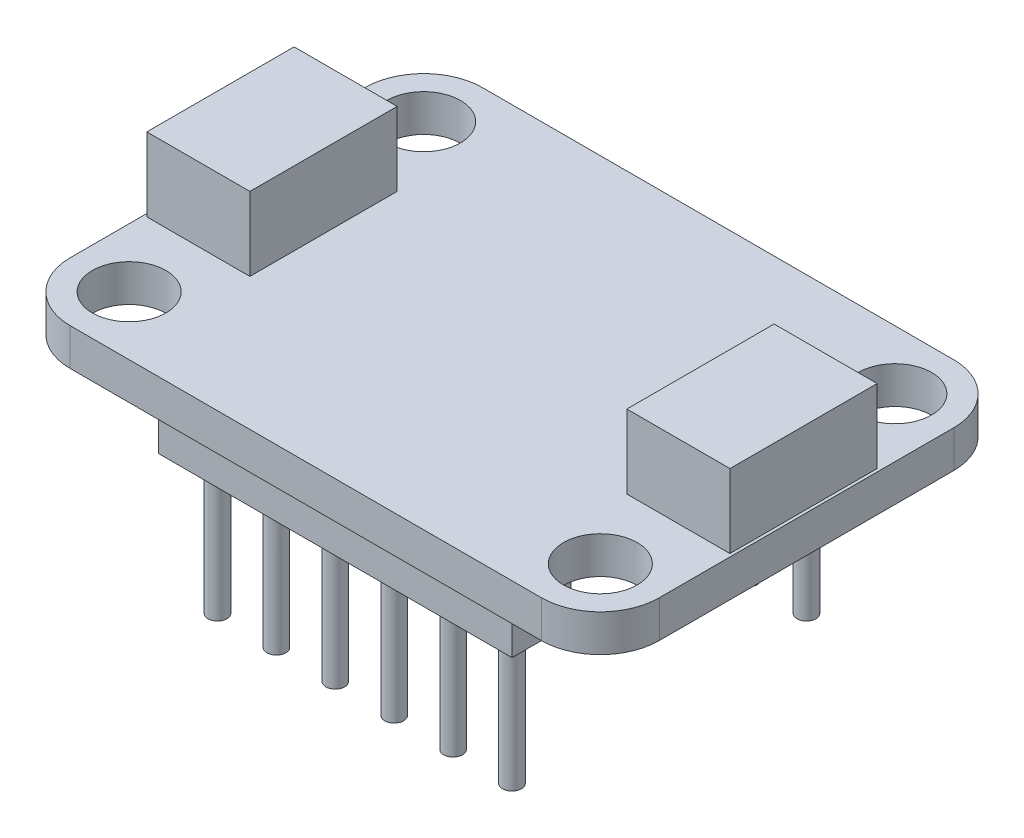
SolidWorks part; units mm, degrees
ref_plane "Front Plane" through (0, 0, 0) normal (0, 0, 1) x (1, 0, 0)
ref_plane "Top Plane" through (0, 0, 0) normal (0, 1, 0) x (1, 0, 0)
ref_plane "Right Plane" through (0, 0, 0) normal (1, 0, 0) x (0, 0, -1)
sketch "Sketch1" plane through (0, 0, 0) normal (0, 1, 0) x (1, 0, 0)
  line L1 (-12.7, -8.89) -> (12.7, -8.89)
  line L2 (-12.7, -8.89) -> (-12.7, 8.89)
  line L3 (-12.7, 8.89) -> (12.7, 8.89)
  line L4 (12.7, -8.89) -> (12.7, 8.89)
  line L5 (-12.7, -8.89) -> (12.7, 8.89) construction
  line L6 (-12.7, 8.89) -> (12.7, -8.89) construction
  point P0 (0, 0)
  dimension "D1" = 25.4
  dimension "D2" = 17.78
extrude "Boss-Extrude1" add sketch "Sketch1" along normal blind 1.6002
sketch "Sketch2" plane through (0, 1.6002, 0) normal (0, 1, 0) x (1, 0, 0)
  line L0 (12.7, 8.89) -> (-12.7, 8.89) construction
  line L1 (-10.16, -6.35) -> (10.16, -6.35) construction
  line L2 (-10.16, -6.35) -> (-10.16, 6.35) construction
  line L3 (-10.16, 6.35) -> (10.16, 6.35) construction
  line L4 (10.16, -6.35) -> (10.16, 6.35) construction
  line L5 (-10.16, -6.35) -> (10.16, 6.35) construction
  line L6 (-10.16, 6.35) -> (10.16, -6.35) construction
  line L7 (-12.7, 8.89) -> (-12.7, -8.89) construction
  line L8 (12.7, -8.89) -> (12.7, 8.89) construction
  line L9 (-12.7, -8.89) -> (12.7, -8.89) construction
  line L10 (-12.7, 6.35) -> (-12.7, 8.89)
  line L11 (-12.7, 8.89) -> (-10.16, 8.89)
  line L12 (10.16, 8.89) -> (12.7, 8.89)
  line L13 (12.7, 8.89) -> (12.7, 6.35)
  line L14 (10.16, -8.89) -> (12.7, -8.89)
  line L15 (12.7, -8.89) -> (12.7, -6.35)
  line L16 (-12.7, -6.35) -> (-12.7, -8.89)
  line L17 (-12.7, -8.89) -> (-10.16, -8.89)
  circle A0 centre (-10.16, 6.35) radius 1.5875
  circle A1 centre (10.16, 6.35) radius 1.5875
  circle A2 centre (10.16, -6.35) radius 1.5875
  circle A3 centre (-10.16, -6.35) radius 1.5875
  arc A4 (-10.16, 8.89) -> (-12.7, 6.35) centre (-10.16, 6.35) ccw
  arc A5 (10.16, 8.89) -> (12.7, 6.35) centre (10.16, 6.35) cw
  arc A6 (12.7, -6.35) -> (10.16, -8.89) centre (10.16, -6.35) cw
  arc A7 (-12.7, -6.35) -> (-10.16, -8.89) centre (-10.16, -6.35) ccw
  point P0 (0, 0)
  dimension "D3" = 3.175
  dimension "D1" = 20.32
  dimension "D2" = 12.7
extrude "Cut-Extrude1" cut sketch "Sketch2" against normal through all both and the other way through all
sketch "Sketch3" plane through (0, 0, 0) normal (0, -1, 0) x (1, 0, 0)
  line L1 (-7.62, 5.08) -> (7.62, 5.08)
  line L2 (-7.62, 5.08) -> (-7.62, 7.62)
  line L3 (-7.62, 7.62) -> (7.62, 7.62)
  line L4 (7.62, 5.08) -> (7.62, 7.62)
  line L5 (-7.62, 5.08) -> (7.62, 7.62) construction
  line L6 (-7.62, 7.62) -> (7.62, 5.08) construction
  point P0 (0, 6.35)
  dimension "D1" = 15.24
  dimension "D2" = 6.35
  dimension "D3" = 2.54
extrude "Boss-Extrude2" add sketch "Sketch3" along normal blind 2.54
sketch "Sketch4" plane through (0, -2.54, 0) normal (0, -1, 0) x (1, 0, 0)
  line L0 (-7.62, 6.35) -> (-6.35, 6.35) construction
  line L1 (-7.62, 7.62) -> (-7.62, 5.08) construction
  line L2 (-6.35, 6.35) -> (-6.35, 5.08) construction
  line L3 (-7.62, 5.08) -> (7.62, 5.08) construction
  circle A0 centre (-6.35, 6.35) radius 0.4064
  dimension "D1" = 0.8128
extrude "Boss-Extrude3" add sketch "Sketch4" along normal blind 5.969 contours A0
pattern_linear "LPattern1" count 6 spacing 2.54 along (1, 0, 0) of "Boss-Extrude3"
mirror "Mirror1" about plane through (0, 0, 0) normal (0, 0, 1) of "LPattern1", "Boss-Extrude3", "Boss-Extrude2"
sketch "Sketch5" plane through (0, 1.6002, 0) normal (0, 1, 0) x (1, 0, 0)
  line L1 (-12.573, 3.175) -> (-8.128, 3.175)
  line L2 (-12.573, 3.175) -> (-12.573, -3.175)
  line L3 (-12.573, -3.175) -> (-8.128, -3.175)
  line L4 (-8.128, 3.175) -> (-8.128, -3.175)
  line L5 (8.128, 3.175) -> (12.573, 3.175)
  line L6 (8.128, 3.175) -> (8.128, -3.175)
  line L7 (8.128, -3.175) -> (12.573, -3.175)
  line L8 (12.573, 3.175) -> (12.573, -3.175)
  line L10 (-12.7, 6.35) -> (-12.7, -6.35) construction
  line L11 (12.7, -6.35) -> (12.7, 6.35) construction
  point P10 (-8.128, 0)
  point P11 (8.128, 0)
  point P14 (0, 0)
  dimension "D1" = 4.445
  dimension "D2" = 6.35
  dimension "D3" = 0.127
  dimension "D4" = 0.127
extrude "Boss-Extrude4" add sketch "Sketch5" along normal blind 3.175
